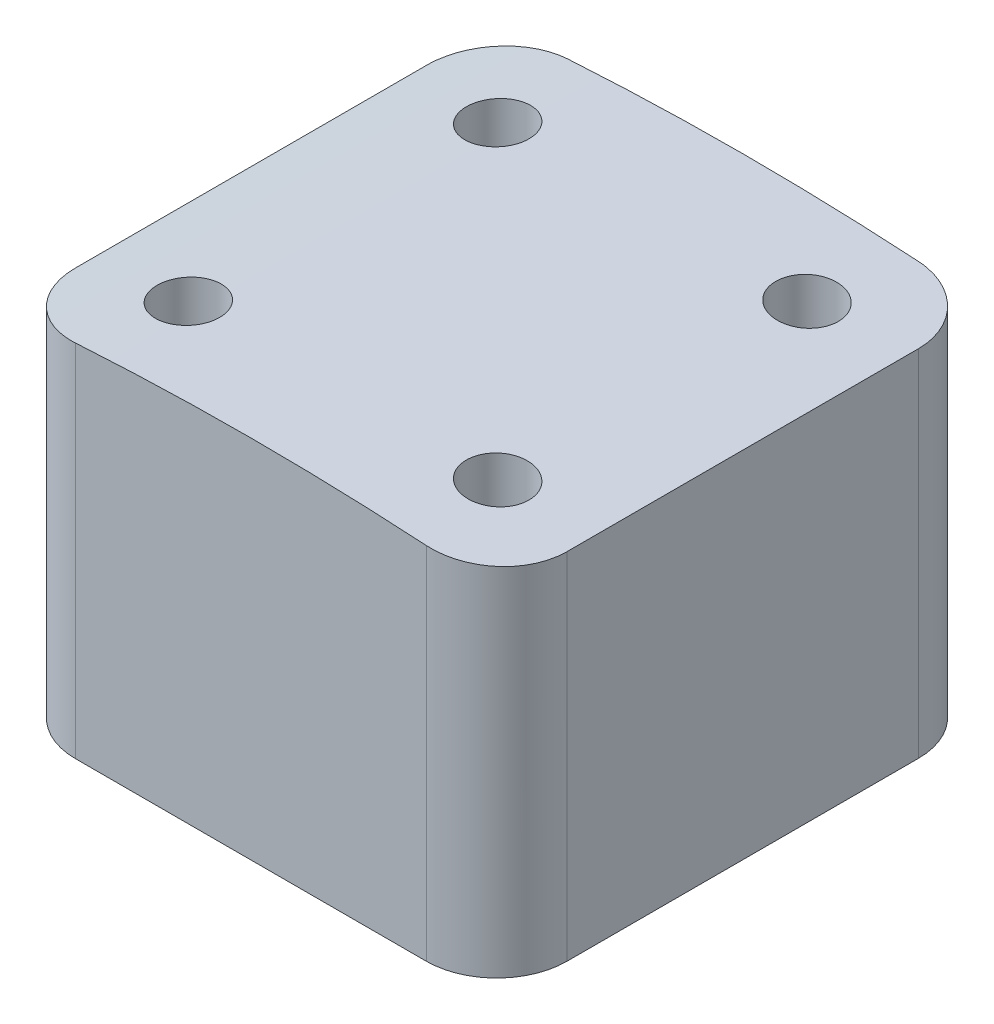
SolidWorks part; units mm, degrees
ref_plane "Front Plane" through (0, 0, 0) normal (0, 0, 1) x (1, 0, 0)
ref_plane "Top Plane" through (0, 0, 0) normal (0, 1, 0) x (1, 0, 0)
ref_plane "Right Plane" through (0, 0, 0) normal (1, 0, 0) x (0, 0, -1)
sketch "Sketch1" plane through (0, 0, 0) normal (0, 0, 1) x (1, 0, 0)
  line L2 (8.8537, 101.3522) -> (8.8537, 88.5344)
  line L3 (8.8537, 88.5344) -> (-8.9026, 88.5344)
  line L4 (-8.9026, 88.5344) -> (-8.9026, 101.3501)
  arc A1 (8.8537, 101.3522) -> (-8.9026, 101.3501) centre (-0.0123, 0.1398) ccw
extrude "Boss-Extrude1" add sketch "Sketch1" along normal blind 8.89 and the other way blind 8.89
sketch "Sketch2" plane through (0, 88.5344, 0) normal (0, -1, 0) x (1, 0, 0)
  circle A0 centre (0, 0) radius 3.175
hole_wizard "1/4 (0.25) Diameter Slot1" positions "Sketch4" profile "Sketch5" size "1/4" standard "ANSI Inch" slot yes
sketch "Sketch4" plane through (0, 88.5344, 0) normal (0, -1, 0) x (-1, 0, 0)
  point P0 (0, 0)
sketch "Sketch5" plane through (0, 88.5344, 0) normal (1, 0, 0) x (0, 0, -1)
  line L0 (0, 0) -> (0, 11.4327)
  line L1 (0, 11.4327) -> (3.175, 9.525)
  line L2 (3.175, 9.525) -> (3.175, 0)
  line L5 (3.175, 0) -> (0, 0)
  line L10 (0, 11.4327) -> (-3.175, 9.525) construction
  line L11 (0, -6.35) -> (0, 107.95) construction
  dimension "Hole Dia." = 6.35
  dimension "Hole Depth" = 9.525
  dimension "Drill Angle" = 118
sketch "Sketch6" plane through (0, 88.5344, 0) normal (0, -1, 0) x (1, 0, 0)
  circle A0 centre (-5.588, -5.588) radius 1.4224
  circle A1 centre (5.588, -5.588) radius 1.4224
  circle A2 centre (5.588, 5.588) radius 1.4224
  circle A3 centre (-5.588, 5.588) radius 1.4224
hole_wizard "Tap Drill for #4-40 Tap1" positions "Sketch8" profile "Sketch9" hole size "#4-40" standard "ANSI Inch" end condition through all
sketch "Sketch8" plane through (0, 88.5344, 0) normal (0, -1, 0) x (-1, 0, 0)
  point P0 (-5.588, 5.588)
  point P3 (5.588, 5.588)
  point P6 (5.588, -5.588)
  point P9 (-5.588, -5.588)
sketch "Sketch9" plane through (5.588, 88.5344, -5.588) normal (1, 0, 0) x (0, 0, -1)
  line L0 (0, 0) -> (0, 13.2054)
  line L1 (0, 13.2054) -> (1.1303, 13.2054)
  line L2 (1.1303, 13.2054) -> (1.1303, 0)
  line L5 (1.1303, 0) -> (0, 0)
  line L11 (0, -6.35) -> (0, 107.95) construction
  dimension "Thru Hole Dia." = 2.2606
  dimension "Thru Hole Depth" = 13.2054
fillet "Fillet1" radius 2.54 4 edges at (-8.9026, 94.9423, 8.89) (-8.9026, 94.9423, -8.89) (8.8537, 94.9433, 8.89) (8.8537, 94.9433, -8.89)
